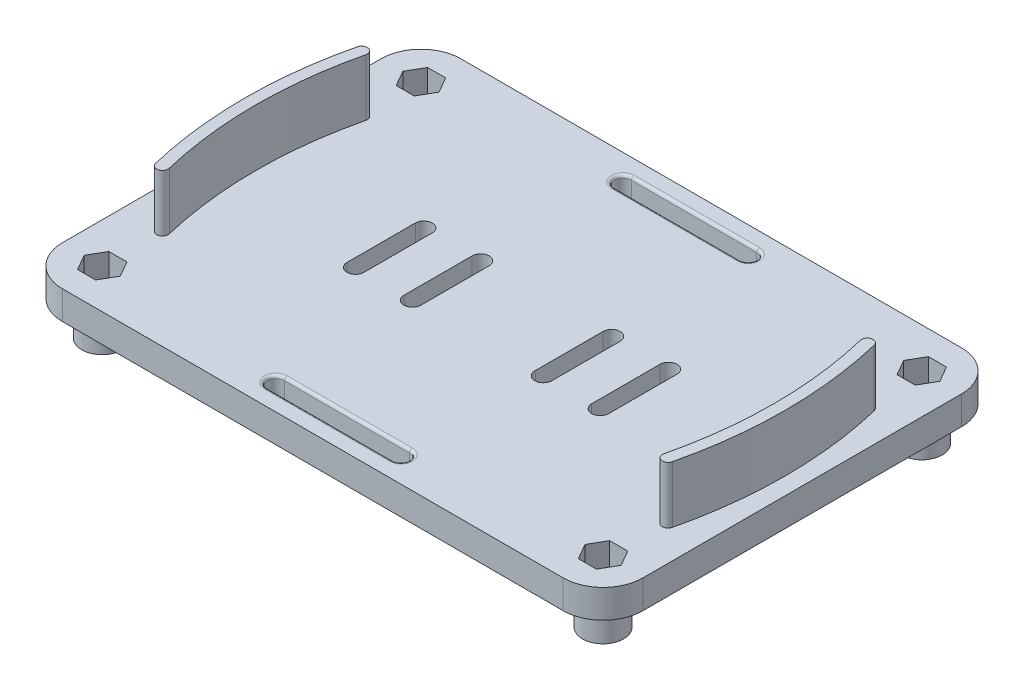
SolidWorks part; units mm, degrees
material "ABS PC"
ref_plane "Front Plane" through (0, 0, 0) normal (0, 0, 1) x (1, 0, 0)
ref_plane "Top Plane" through (0, 0, 0) normal (0, 1, 0) x (1, 0, 0)
ref_plane "Right Plane" through (0, 0, 0) normal (1, 0, 0) x (0, 0, -1)
sketch "Sketch1" plane through (0, 0, 0) normal (0, 1, 0) x (1, 0, 0)
  line L1 (-44, -35) -> (44, -35)
  line L2 (-51, -28) -> (-51, 28)
  line L3 (-44, 35) -> (44, 35)
  line L4 (51, -28) -> (51, 28)
  line L5 (-51, -35) -> (51, 35) construction
  line L6 (-51, 35) -> (51, -35) construction
  arc A0 (44, 35) -> (51, 28) centre (44, 28) cw
  arc A1 (44, -35) -> (51, -28) centre (44, -28) ccw
  arc A2 (-44, -35) -> (-51, -28) centre (-44, -28) cw
  arc A3 (-51, 28) -> (-44, 35) centre (-44, 28) cw
  point P0 (0, 0)
  dimension "D3" = 7
  dimension "D1" = 102
  dimension "D2" = 70
extrude "Boss-Extrude1" add sketch "Sketch1" along normal blind 5 contours L3 A0 L4 A1 L1 A2 L2 A3
sketch "Sketch2" plane through (0, 5, 0) normal (0, 1, 0) x (1, 0, 0)
  line L4 (-11, -30.5) -> (11, -30.5) construction
  line L5 (-11, -29) -> (11, -29)
  line L6 (-11, -32) -> (11, -32)
  line L7 (-44, -35) -> (44, -35) construction
  line L8 (-11.5, 6) -> (-11.5, -6) construction
  line L10 (0, -87.4721) -> (0, 26.4721) construction
  line L11 (-29.5651, 0) -> (32.1867, 0) construction
  line L18 (-11, 30.5) -> (11, 30.5) construction
  line L19 (-11, 29) -> (11, 29)
  line L20 (-11, 32) -> (11, 32)
  line L21 (-21.5, 6) -> (-21.5, -6) construction
  line L22 (-20, 6) -> (-20, -6)
  line L23 (-23, 6) -> (-23, -6)
  line L24 (-10, 6) -> (-10, -6)
  line L25 (-13, 6) -> (-13, -6)
  line L26 (11.5, 6) -> (11.5, -6) construction
  line L27 (10, 6) -> (10, -6)
  line L28 (13, 6) -> (13, -6)
  line L29 (21.5, 6) -> (21.5, -6) construction
  line L30 (20, 6) -> (20, -6)
  line L31 (23, 6) -> (23, -6)
  arc A0 (-11, -29) -> (-11, -32) centre (-11, -30.5) ccw
  arc A1 (11, -32) -> (11, -29) centre (11, -30.5) ccw
  arc A6 (-11, 29) -> (-11, 32) centre (-11, 30.5) cw
  arc A7 (11, 32) -> (11, 29) centre (11, 30.5) cw
  arc A8 (-20, 6) -> (-23, 6) centre (-21.5, 6) ccw
  arc A9 (-23, -6) -> (-20, -6) centre (-21.5, -6) ccw
  arc A10 (-10, 6) -> (-13, 6) centre (-11.5, 6) ccw
  arc A11 (-13, -6) -> (-10, -6) centre (-11.5, -6) ccw
  arc A12 (10, 6) -> (13, 6) centre (11.5, 6) cw
  arc A13 (13, -6) -> (10, -6) centre (11.5, -6) cw
  arc A14 (20, 6) -> (23, 6) centre (21.5, 6) cw
  arc A15 (23, -6) -> (20, -6) centre (21.5, -6) cw
  point P2 (0, -30.5)
  point P32 (0, 30.5)
  point P39 (-21.5, 0)
  point P46 (-11.5, 0)
  point P54 (11.5, 0)
  point P61 (21.5, 0)
  dimension "D1" = 25
  dimension "D5" = 15
  dimension "D2" = 3
  dimension "D3" = 3
  dimension "D6" = 3
  dimension "D7" = 20
  dimension "D8" = 10
extrude "Cut-Extrude1" cut sketch "Sketch2" against normal blind 12
sketch "Sketch3" plane through (0, 5, 0) normal (0, 1, 0) x (1, 0, 0)
  line L0 (-51, -28) -> (-51, 28) construction
  line L2 (51, -28) -> (51, 28) construction
  arc A0 (-43.9298, 17.5) -> (-43.9298, -17.5) centre (29, 0) ccw construction
  arc A1 (-44.9022, 17.7333) -> (-44.9022, -17.7333) centre (29, 0) ccw
  arc A2 (-42.9574, 17.2667) -> (-42.9574, -17.2667) centre (29, 0) ccw
  arc A3 (-44.9022, 17.7333) -> (-42.9574, 17.2667) centre (-43.9298, 17.5) cw
  arc A4 (-44.9022, -17.7333) -> (-42.9574, -17.2667) centre (-43.9298, -17.5) ccw
  arc A5 (44.9298, 17.5) -> (44.9298, -17.5) centre (-28, 0) cw construction
  arc A6 (43.9574, 17.2667) -> (43.9574, -17.2667) centre (-28, 0) cw
  arc A7 (45.9022, 17.7333) -> (45.9022, -17.7333) centre (-28, 0) cw
  arc A8 (43.9574, 17.2667) -> (45.9022, 17.7333) centre (44.9298, 17.5) cw
  arc A9 (43.9574, -17.2667) -> (45.9022, -17.7333) centre (44.9298, -17.5) ccw
  point P7 (-46, 0)
  point P18 (47, 0)
  dimension "D2" = 75
  dimension "D3" = 35
  dimension "D6" = 35
  dimension "D7" = 4
  dimension "D8" = 75
  dimension "D1" = 5
  dimension "D4" = 1
  dimension "D5" = 1
  dimension "D9" = 1
  dimension "D10" = 1
extrude "Boss-Extrude2" add sketch "Sketch3" along normal blind 10
fillet "Fillet1" radius 0.5 16 edges at (0, 0, -29) (12.5, 0, -30.5) (0, 0, -32) (12.5, 0, 30.5) (0, 0, 29) (-12.5, 0, 30.5) (12.5, 5, 30.5) (0, 5, 32) (-12.5, 5, 30.5) (12.5, 5, -30.5) (0, 5, -29) (-12.5, 5, -30.5) (-12.5, 0, -30.5) (0, 0, 32) (0, 5, 29) (0, 5, -32)
sketch "Sketch4" plane through (0, 5, 0) normal (0, 1, 0) x (1, 0, 0)
  circle A0 centre (-44, 28) radius 3.6
  circle A1 centre (-44, -28) radius 3.6
  circle A2 centre (44, -28) radius 3.6
  circle A3 centre (44, 28) radius 3.6
  point P0 (-44, 28)
  dimension "D1" = 7.2
extrude "Boss-Extrude3" add sketch "Sketch4" against normal blind 6 from surface at -5 starting at face at (0, 0, -30.5)
sketch "Sketch6" plane through (0, 5, 0) normal (0, 1, 0) x (1, 0, 0)
  line L0 (-5.067, 0) -> (5.6178, 0) construction
  circle A0 centre (-44, 28) radius 1.6
  circle A1 centre (44, 28) radius 1.6
  circle A2 centre (44, -28) radius 1.6
  circle A3 centre (-44, -28) radius 1.6
  dimension "D1" = 3.2
extrude "Cut-Extrude2" cut sketch "Sketch6" against normal through all contours A0
sketch "Sketch7" plane through (0, 5, 0) normal (0, 1, 0) x (1, 0, 0)
  line L0 (-44, 35) -> (44, 35) construction
  line L1 (-42.4123, 30.75) -> (-45.5877, 30.75)
  line L2 (-45.5877, 30.75) -> (-47.1754, 28)
  line L3 (-47.1754, 28) -> (-45.5877, 25.25)
  line L4 (-45.5877, 25.25) -> (-42.4123, 25.25)
  line L5 (-42.4123, 25.25) -> (-40.8246, 28)
  line L6 (-40.8246, 28) -> (-42.4123, 30.75)
  line L7 (0, 12.3887) -> (0, -8.0494) construction
  line L8 (-4.7345, 0) -> (6.2511, 0) construction
  line L9 (40.8246, 28) -> (42.4123, 30.75)
  line L10 (42.4123, 25.25) -> (40.8246, 28)
  line L11 (45.5877, 25.25) -> (42.4123, 25.25)
  line L12 (47.1754, 28) -> (45.5877, 25.25)
  line L13 (45.5877, 30.75) -> (47.1754, 28)
  line L14 (42.4123, 30.75) -> (45.5877, 30.75)
  line L15 (42.4123, -30.75) -> (45.5877, -30.75)
  line L16 (45.5877, -30.75) -> (47.1754, -28)
  line L17 (47.1754, -28) -> (45.5877, -25.25)
  line L18 (45.5877, -25.25) -> (42.4123, -25.25)
  line L19 (42.4123, -25.25) -> (40.8246, -28)
  line L20 (40.8246, -28) -> (42.4123, -30.75)
  line L21 (-40.8246, -28) -> (-42.4123, -30.75)
  line L22 (-42.4123, -25.25) -> (-40.8246, -28)
  line L23 (-45.5877, -25.25) -> (-42.4123, -25.25)
  line L24 (-47.1754, -28) -> (-45.5877, -25.25)
  line L25 (-45.5877, -30.75) -> (-47.1754, -28)
  line L26 (-42.4123, -30.75) -> (-45.5877, -30.75)
  circle A1 centre (-44, 28) radius 2.75 construction
  circle A2 centre (44, 28) radius 2.75 construction
  circle A3 centre (44, -28) radius 2.75 construction
  circle A4 centre (-44, -28) radius 2.75 construction
  dimension "D1" = 5.5
extrude "Cut-Extrude3" cut sketch "Sketch7" against normal blind 6
